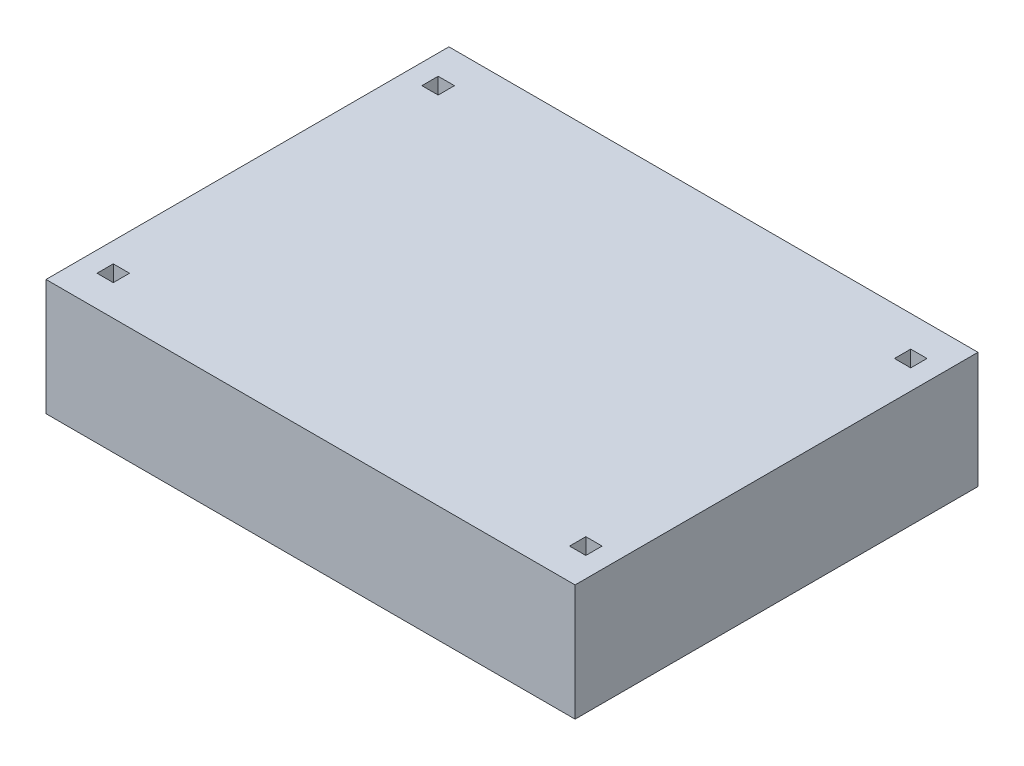
SolidWorks part; units mm, degrees
ref_plane "Front Plane" through (0, 0, 0) normal (0, 0, 1) x (1, 0, 0)
ref_plane "Top Plane" through (0, 0, 0) normal (0, 1, 0) x (1, 0, 0)
ref_plane "Right Plane" through (0, 0, 0) normal (1, 0, 0) x (0, 0, -1)
sketch "Sketch1" plane through (0, 0, 0) normal (0, 1, 0) x (1, 0, 0)
  line L1 (22.75, -17.325) -> (-22.75, -17.325)
  line L2 (22.75, -17.325) -> (22.75, 17.325)
  line L3 (22.75, 17.325) -> (-22.75, 17.325)
  line L4 (-22.75, -17.325) -> (-22.75, 17.325)
  line L5 (22.75, -17.325) -> (-22.75, 17.325) construction
  line L6 (22.75, 17.325) -> (-22.75, -17.325) construction
  point P0 (0, 0)
  dimension "D1" = 45.5
  dimension "D2" = 34.65
extrude "Breadboard Base" add sketch "Sketch1" along normal blind 10
sketch "Sketch2" plane through (0, 10, 0) normal (0, 1, 0) x (1, 0, 0)
  line L2 (-21.02, 14.67) -> (-19.62, 14.67)
  line L3 (-21.02, 14.67) -> (-21.02, 13.27)
  line L4 (-21.02, 13.27) -> (-19.62, 13.27)
  line L6 (0, 0) -> (-26.2979, 0) construction
  line L7 (0, 0) -> (0, 20.1783) construction
  line L8 (-19.62, 14.67) -> (-19.62, 13.27)
  line L9 (-21.02, 14.67) -> (-19.62, 13.27) construction
  line L10 (-21.02, 13.27) -> (-19.62, 14.67) construction
  line L11 (21.02, 13.27) -> (19.62, 13.27)
  line L12 (21.02, 13.27) -> (21.02, 14.67)
  line L13 (21.02, 14.67) -> (19.62, 14.67)
  line L14 (19.62, 13.27) -> (19.62, 14.67)
  line L15 (21.02, 13.27) -> (19.62, 14.67) construction
  line L16 (21.02, 14.67) -> (19.62, 13.27) construction
  line L17 (-21.02, -14.67) -> (-19.62, -14.67)
  line L18 (-21.02, -14.67) -> (-21.02, -13.27)
  line L19 (-21.02, -13.27) -> (-19.62, -13.27)
  line L20 (-19.62, -14.67) -> (-19.62, -13.27)
  line L21 (-21.02, -14.67) -> (-19.62, -13.27) construction
  line L22 (-21.02, -13.27) -> (-19.62, -14.67) construction
  line L23 (21.02, -14.67) -> (19.62, -14.67)
  line L24 (21.02, -14.67) -> (21.02, -13.27)
  line L25 (21.02, -13.27) -> (19.62, -13.27)
  line L26 (19.62, -14.67) -> (19.62, -13.27)
  line L27 (21.02, -14.67) -> (19.62, -13.27) construction
  line L28 (21.02, -13.27) -> (19.62, -14.67) construction
  point P0 (-20.32, 13.97)
  point P6 (20.32, 13.97)
  point P14 (-20.32, -13.97)
  point P19 (20.32, -13.97)
  dimension "D1" = 1.4
  dimension "D2" = 27.94
  dimension "D3" = 40.64
extrude "Holes for Pins" cut sketch "Sketch2" against normal blind 6.5
ref_plane "Plane1" through (-20.32, 0, 0) normal (1, 0, 0) x (0, 0, -1)
ref_plane "Plane2" through (0, 0, -13.97) normal (0, 0, 1) x (1, 0, 0)
